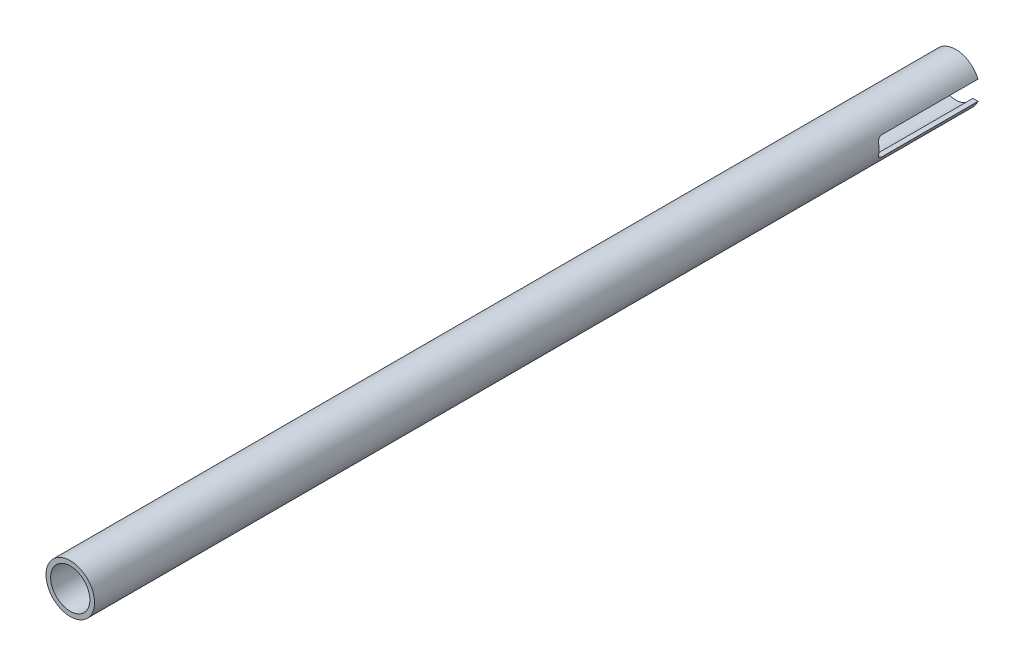
SolidWorks part; units mm, degrees
material "AISI 4130 Steel, annealed at 865C"
ref_plane "Front Plane" through (0, 0, 0) normal (0, 0, 1) x (1, 0, 0)
ref_plane "Top Plane" through (0, 0, 0) normal (0, 1, 0) x (1, 0, 0)
ref_plane "Right Plane" through (0, 0, 0) normal (1, 0, 0) x (0, 0, -1)
sketch "Sketch1" plane through (0, 0, 0) normal (0, 0, 1) x (1, 0, 0)
  circle A0 centre (0, 0) radius 6.477
  circle A1 centre (0, 0) radius 8.001
  dimension "D1" = 12.954
  dimension "D2" = 16.002
extrude "Boss-Extrude1" add sketch "Sketch1" along normal blind 292.1
sketch "Sketch2" plane through (0, 0, 0) normal (1, 0, 0) x (0, 0, -1)
  line L0 (0, 3.175) -> (-31.75, 3.175)
  line L1 (0, 55) -> (0, -55) construction
  line L2 (-31.75, -3.175) -> (0, -3.175)
  line L3 (-33.274, 1.651) -> (-33.274, -1.651)
  line L4 (0, -8.001) -> (0, 8.001) construction
  arc A0 (-33.274, 1.651) -> (-31.75, 3.175) centre (-31.75, 1.651) cw
  arc A1 (-31.75, -3.175) -> (-33.274, -1.651) centre (-31.75, -1.651) cw
  dimension "D5" = 31.75
  dimension "D6" = 33.274
  dimension "D1" = 33.274
  dimension "D2" = 31.75
  dimension "D3" = 6.35
  dimension "D4" = 3.175
extrude "Cut-Extrude1" cut sketch "Sketch2" against normal through all both and the other way through all
